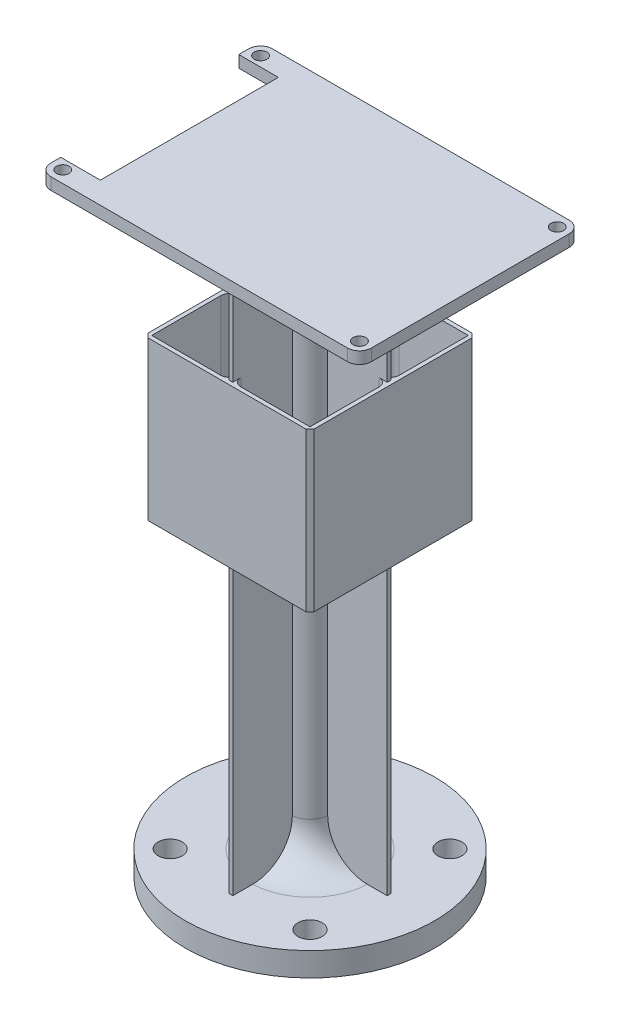
SolidWorks part; units mm, degrees
ref_plane "前视基准面" through (0, 0, 0) normal (0, 0, 1) x (1, 0, 0)
ref_plane "上视基准面" through (0, 0, 0) normal (0, 1, 0) x (1, 0, 0)
ref_plane "右视基准面" through (0, 0, 0) normal (1, 0, 0) x (0, 0, -1)
other "Configuration Table"
sketch "草图1" plane through (0, 0, 0) normal (0, 1, 0) x (1, 0, 0)
  line L0 (0, 0) -> (33.8434, 33.8434) construction
  line L1 (0, 0) -> (-36.0984, 36.0984) construction
  circle A0 centre (0, 0) radius 31.5
  circle A1 centre (-17.6777, 17.6777) radius 3.05
  circle A2 centre (17.6777, 17.6777) radius 3.05
  circle A3 centre (-17.6777, -17.6777) radius 3.05
  circle A4 centre (17.6777, -17.6777) radius 3.05
  circle A5 centre (0, 0) radius 25 construction
  dimension "D1" = 63
  dimension "D2" = 6.1
  dimension "D3" = 6.1
  dimension "D4" = 6.1
  dimension "D5" = 6.1
  dimension "D6" = 50
extrude "凸台-拉伸3" add sketch "草图1" along normal blind 6
sketch "草图4" plane through (0, 0, 0) normal (0, -1, 0) x (1, 0, 0)
  circle A0 centre (0, 0) radius 5
  dimension "D1" = 10
extrude "凸台-拉伸5" add sketch "草图4" against normal blind 145.4
sketch "草图8" plane through (0, 0, 0) normal (1, 0, 0) x (0, 0, -1)
  line L0 (0, 145.4) -> (0, 0)
  line L1 (5, 145.4) -> (-5, 145.4) construction
  line L2 (-31.5, 0) -> (31.5, 0) construction
  line L3 (0, 0) -> (20, 0)
  line L6 (0, 145.4) -> (20, 145.4)
  line L7 (20, 145.4) -> (20, 0)
  dimension "D1" = 20
  dimension "D2" = 20
extrude "凸台-拉伸8" add sketch "草图8" along normal mid plane 1 contours L0 L3 L7 L6
pattern_circular "阵列(圆周)1" count 4 over 360 about axis through (0, 0, 0) along (0, 1, 0) of "凸台-拉伸8"
fillet "圆角1" radius 10 4 edges at (-3.5355, 6, -3.5355) (3.5355, 6, -3.5355) (-3.5355, 6, 3.5355) (3.5355, 6, 3.5355)
sketch "草图10" plane through (0, 145.4, 0) normal (0, 1, 0) x (1, 0, 0)
  line L5 (-37.4995, -27.9995) -> (37.4995, -27.9995)
  line L6 (40.4995, -24.9995) -> (40.4995, 24.9995)
  line L10 (37.4995, 27.9995) -> (-37.4995, 27.9995)
  line L11 (-40.4995, 24.9995) -> (-40.4995, -24.9995)
  line L12 (-37.4995, 24.9995) -> (37.4995, -24.9995) construction
  line L13 (37.4995, 24.9995) -> (-37.4995, -24.9995) construction
  line L14 (-37.4995, 27.9995) -> (-37.4995, -27.9995) construction
  line L15 (-40.4995, 24.9995) -> (40.4995, 24.9995) construction
  line L16 (37.4995, 27.9995) -> (37.4995, -27.9995) construction
  line L17 (40.4995, -24.9995) -> (-40.4995, -24.9995) construction
  arc A5 (-40.4995, -24.9995) -> (-37.4995, -27.9995) centre (-37.4995, -24.9995) ccw
  arc A6 (37.4995, -27.9995) -> (40.4995, -24.9995) centre (37.4995, -24.9995) ccw
  arc A7 (40.4995, 24.9995) -> (37.4995, 27.9995) centre (37.4995, 24.9995) ccw
  arc A8 (-37.4995, 27.9995) -> (-40.4995, 24.9995) centre (-37.4995, 24.9995) ccw
  dimension "D2" = 3
  dimension "D3" = 3
  dimension "D7" = 74.9989
  dimension "D8" = 49.9989
extrude "凸台-拉伸10" add sketch "草图10" along normal blind 3
sketch "草图11" plane through (0, 148.4, 0) normal (0, 1, 0) x (1, 0, 0)
  line L0 (-37.4995, 27.9995) -> (-37.4995, -27.9995) construction
  line L1 (-40.4995, 24.9995) -> (40.4995, 24.9995) construction
  line L2 (37.4995, 27.9995) -> (37.4995, -27.9995) construction
  line L3 (-40.4995, -24.9995) -> (40.4995, -24.9995) construction
  circle A0 centre (-37.4995, 24.9995) radius 1.6
  circle A1 centre (-37.4995, -24.9995) radius 1.6
  circle A2 centre (37.4995, 24.9995) radius 1.6
  circle A3 centre (37.4995, -24.9995) radius 1.6
  dimension "D1" = 3.2
  dimension "D2" = 3.2
  dimension "D3" = 3.2
  dimension "D4" = 3.2
extrude "切除-拉伸1" cut sketch "草图11" against normal blind 3
sketch "草图12" plane through (0, 148.4, 0) normal (0, 1, 0) x (1, 0, 0)
  line L0 (-40.4995, 24.9995) -> (-40.4995, -24.9995) construction
  line L1 (-40.4995, 22.5) -> (-30.4995, 22.5)
  line L2 (-40.4995, 22.5) -> (-40.4995, -22.5)
  line L3 (-40.4995, -22.5) -> (-30.4995, -22.5)
  line L4 (-30.4995, 22.5) -> (-30.4995, -22.5)
  line L6 (-43.8763, 0) -> (43.1668, 0) construction
  line L7 (-40.4995, 22.5) -> (-30.4995, -22.5) construction
  line L8 (-30.4995, 22.5) -> (-40.4995, -22.5) construction
  point P8 (-35.4995, 0)
  dimension "D1" = 10
  dimension "D2" = 45
extrude "切除-拉伸2" cut sketch "草图12" against normal blind 3
fillet "圆角3" radius 10 4 edges at (3.5355, 145.4, 3.5355) (-3.5355, 145.4, 3.5355) (3.5355, 145.4, -3.5355) (-3.5355, 145.4, -3.5355)
sketch "草图18" plane through (0, 148.4, 0) normal (0, 1, 0) x (1, 0, 0)
  line L0 (-20, 21) -> (-21, 20)
  line L5 (-20, 21) -> (20, 21)
  line L6 (-20, 21) -> (-20, -21) construction
  line L7 (-20, -21) -> (20, -21)
  line L8 (20, 21) -> (20, -21) construction
  line L9 (-20, 21) -> (20, -21) construction
  line L10 (-20, -21) -> (20, 21) construction
  line L11 (-21, 20) -> (21, 20) construction
  line L12 (-21, 20) -> (-21, -20)
  line L13 (-21, -20) -> (21, -20) construction
  line L14 (21, 20) -> (21, -20)
  line L15 (-21, 20) -> (21, -20) construction
  line L16 (-21, -20) -> (21, 20) construction
  line L17 (20, 21) -> (21, 20)
  line L18 (-21, -20) -> (-20, -21)
  line L19 (20, -21) -> (21, -20)
  line L21 (-20, 20) -> (20, 20)
  line L22 (-20, 20) -> (-20, -20)
  line L23 (-20, -20) -> (20, -20)
  line L24 (20, 20) -> (20, -20)
  line L25 (-20, 20) -> (20, -20) construction
  line L26 (-20, -20) -> (20, 20) construction
  point P0 (0, 0)
  point P6 (0, 0)
  point P8 (0, 0)
  dimension "D1" = 42
  dimension "D2" = 40
  dimension "D3" = 42
  dimension "D4" = 40
  dimension "D5" = 40
  dimension "D6" = 40
extrude "凸台-拉伸18" add sketch "草图18" against normal blind 70
sketch "草图19" plane through (21, 0, 0) normal (1, 0, 0) x (0, 0, -1)
  line L0 (-21, 78.4) -> (-21, 145.4) construction
  line L1 (-21, 145.4) -> (21, 145.4)
  line L2 (-21, 145.4) -> (-21, 118.4)
  line L3 (-21, 118.4) -> (21, 118.4)
  line L4 (21, 145.4) -> (21, 118.4)
  line L5 (21, 78.4) -> (21, 145.4) construction
  line L6 (-24.9995, 145.4) -> (24.9995, 145.4) construction
  line L7 (-20, 78.4) -> (20, 78.4) construction
  dimension "D1" = 40
extrude "切除-拉伸3" cut sketch "草图19" against normal blind 1
sketch "草图20" plane through (0, 0, -21) normal (0, 0, -1) x (-1, 0, 0)
  line L1 (-21, 118.4) -> (21, 118.4)
  line L2 (-21, 118.4) -> (-21, 145.4)
  line L3 (-21, 145.4) -> (21, 145.4)
  line L4 (21, 118.4) -> (21, 145.4)
extrude "切除-拉伸4" cut sketch "草图20" against normal blind 1
sketch "草图21" plane through (-21, 0, 0) normal (-1, 0, 0) x (0, 0, 1)
  line L1 (-21, 118.4) -> (21, 118.4)
  line L2 (-21, 118.4) -> (-21, 145.4)
  line L3 (-21, 145.4) -> (21, 145.4)
  line L4 (21, 118.4) -> (21, 145.4)
extrude "切除-拉伸5" cut sketch "草图21" against normal blind 1
sketch "草图22" plane through (0, 0, 21) normal (0, 0, 1) x (1, 0, 0)
  line L1 (-21, 118.4) -> (20, 118.4)
  line L2 (-21, 118.4) -> (-21, 145.4)
  line L3 (-21, 145.4) -> (20, 145.4)
  line L4 (20, 118.4) -> (20, 145.4)
extrude "切除-拉伸6" cut sketch "草图22" against normal blind 1
fillet "圆角4" radius 2 8 edges at (0.5, 98.4, 20) (-0.5, 98.4, 20) (20, 98.4, 0.5) (20, 98.4, -0.5) (0.5, 98.4, -20) (-0.5, 98.4, -20) (-20, 98.4, -0.5) (-20, 98.4, 0.5)
